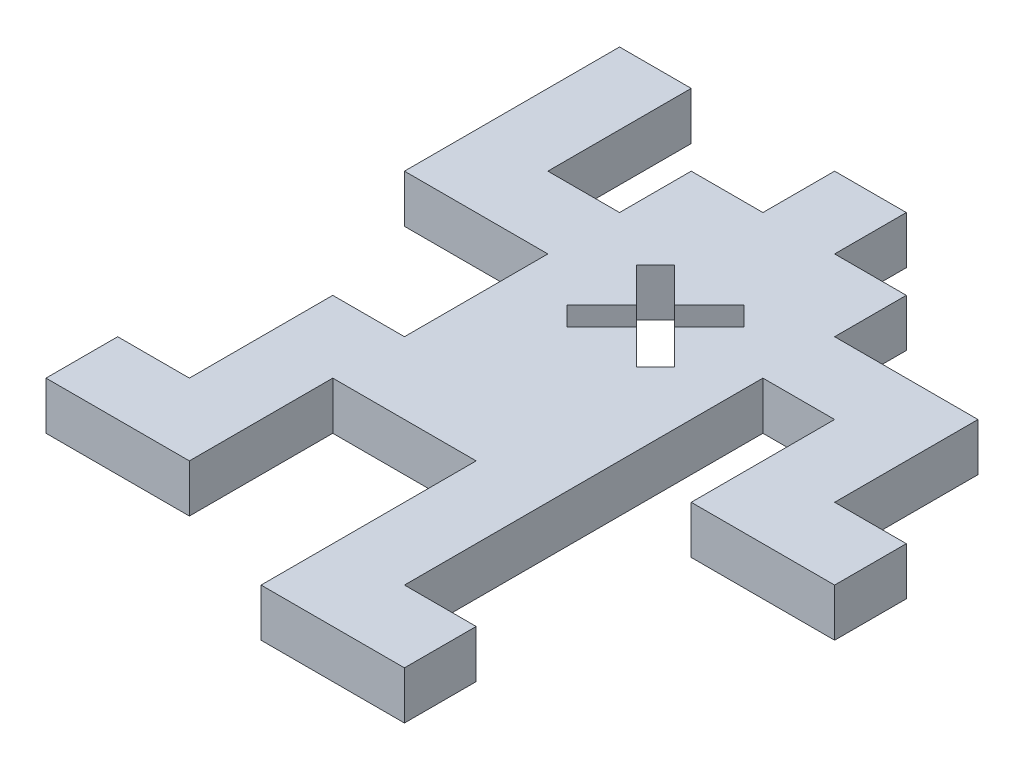
SolidWorks part; units mm, degrees
ref_plane "Front Plane" through (0, 0, 0) normal (0, 0, 1) x (1, 0, 0)
ref_plane "Top Plane" through (0, 0, 0) normal (0, 1, 0) x (1, 0, 0)
ref_plane "Right Plane" through (0, 0, 0) normal (1, 0, 0) x (0, 0, -1)
sketch "Sketch1" plane through (0, 0, 0) normal (0, 1, 0) x (1, 0, 0)
  line L0 (-11.25, 11.25) -> (-18.75, 11.25)
  line L1 (-11.25, 18.75) -> (11.25, 18.75)
  line L2 (-11.25, 18.75) -> (-11.25, -18.75)
  line L3 (-11.25, -18.75) -> (11.25, -18.75)
  line L4 (11.25, 18.75) -> (11.25, -18.75)
  line L5 (-11.25, 18.75) -> (11.25, -18.75) construction
  line L6 (-11.25, -18.75) -> (11.25, 18.75) construction
  line L7 (-3.75, 18.75) -> (3.75, 18.75)
  line L8 (-3.75, 18.75) -> (-3.75, 26.25)
  line L9 (-3.75, 26.25) -> (3.75, 26.25)
  line L10 (3.75, 18.75) -> (3.75, 26.25)
  line L11 (-18.75, 11.25) -> (-18.75, 26.25)
  line L12 (-18.75, 26.25) -> (-26.25, 26.25)
  line L13 (-26.25, 26.25) -> (-26.25, 3.75)
  line L14 (-26.25, 3.75) -> (-11.25, 3.75)
  line L15 (11.25, 11.25) -> (26.25, 11.25)
  line L16 (26.25, 11.25) -> (26.25, -3.75)
  line L17 (26.25, -3.75) -> (33.75, -3.75)
  line L18 (33.75, -3.75) -> (33.75, -11.25)
  line L19 (33.75, -11.25) -> (18.75, -11.25)
  line L20 (18.75, -11.25) -> (18.75, 3.75)
  line L21 (18.75, 3.75) -> (11.25, 3.75)
  line L22 (11.25, -18.75) -> (11.25, -33.75)
  line L23 (11.25, -33.75) -> (18.75, -33.75)
  line L24 (18.75, -33.75) -> (18.75, -41.25)
  line L25 (18.75, -41.25) -> (3.75, -41.25)
  line L26 (3.75, -41.25) -> (3.75, -18.75)
  line L27 (-11.25, -18.75) -> (-11.25, -33.75)
  line L28 (-11.25, -33.75) -> (-26.25, -33.75)
  line L29 (-26.25, -33.75) -> (-26.25, -26.25)
  line L30 (-26.25, -26.25) -> (-18.75, -26.25)
  line L31 (-18.75, -26.25) -> (-18.75, -11.25)
  line L32 (-18.75, -11.25) -> (-11.25, -11.25)
  point P0 (0, 0)
  dimension "D1" = 37.5
  dimension "D2" = 22.5
  dimension "D3" = 7.5
  dimension "D4" = 7.5
  dimension "D5" = 7.5
  dimension "D6" = 7.5
  dimension "D7" = 7.5
  dimension "D8" = 7.5
  dimension "D9" = 15
  dimension "D10" = 15
  dimension "D11" = 7.5
  dimension "D12" = 7.5
  dimension "D13" = 15
  dimension "D14" = 22.5
  dimension "D15" = 22.5
  dimension "D16" = 7.5
  dimension "D17" = 15
  dimension "D18" = 15
  dimension "D19" = 15
  dimension "D20" = 7.5
  dimension "D21" = 15
  dimension "D22" = 15
  dimension "D23" = 7.5
extrude "Boss-Extrude1" add sketch "Sketch1" along normal blind 5 contours L13 L14 L2 L0 L11 L12 | L4 L1 L2 L3 | L1 L10 L9 L8 | L21 L20 L19 L18 L17 L16 L15 L4 | L26 L25 L24 L23 L22 L3 | L32 L31 L30 L29 L28 L27 L2
sketch "Sketch2" plane through (0, 5, 0) normal (0, 1, 0) x (1, 0, 0)
  line L0 (-11.25, 11.25) -> (11.25, 11.25) construction
  line L3 (-11.25, -3.75) -> (11.25, -3.75) construction
  line L4 (-11.25, 3.75) -> (-11.25, -11.25) construction
  line L5 (11.25, 3.75) -> (11.25, -33.75) construction
  line L6 (0, 11.25) -> (0, -3.75) construction
  line L7 (0, 5.75) -> (-3.625, 9.375)
  line L8 (-3.625, 9.375) -> (-5.625, 7.375)
  line L9 (-5.625, 7.375) -> (-2, 3.75)
  line L10 (-2, 3.75) -> (-5.625, 0.125)
  line L11 (-5.625, 0.125) -> (-3.625, -1.875)
  line L12 (-3.625, -1.875) -> (0, 1.75)
  line L13 (0, 5.75) -> (0, 1.75) construction
  line L14 (3.625, -1.875) -> (0, 1.75)
  line L15 (5.625, 0.125) -> (3.625, -1.875)
  line L16 (2, 3.75) -> (5.625, 0.125)
  line L17 (5.625, 7.375) -> (2, 3.75)
  line L18 (3.625, 9.375) -> (5.625, 7.375)
  line L19 (0, 5.75) -> (3.625, 9.375)
  point P25 (0, 3.75)
  dimension "D1" = 45
  dimension "D3" = 1.875
  dimension "D4" = 4
  dimension "D2" = 2
extrude "Cut-Extrude1" cut sketch "Sketch2" against normal through all
equation "\"Square Width\" = 7.5mm"
equation "\"Square Height\"= 7.5mm"
equation "\"Tolerance\"= 1mm"
equation "\"Block Height\" = 5mm"
equation "\"Base Height\"= 10mm"
equation "\"D1@Sketch1\"=\"Square Height\"*5"
equation "\"D2@Sketch1\"=\"Square Width\"*3"
equation "\"D3@Sketch1\"=\"Square Width\""
equation "\"D4@Sketch1\"=\"Square Height\""
equation "\"D5@Sketch1\"=\"Square Width\""
equation "\"D6@Sketch1\"=\"Square Height\""
equation "\"D7@Sketch1\"=\"Square Height\""
equation "\"D8@Sketch1\"=\"Square Width\""
equation "\"D9@Sketch1\"=\"Square Width\"*2"
equation "\"D10@Sketch1\"=\"Square Width\"*2"
equation "\"D11@Sketch1\"=\"Square Width\""
equation "\"D12@Sketch1\"=\"Square Height\""
equation "\"D13@Sketch1\"=\"Square Width\"*2"
equation "\"D14@Sketch1\"=\"Square Height\"*3"
equation "\"D15@Sketch1\"=\"Square Height\"*3"
equation "\"D16@Sketch1\"=\"Square Width\""
equation "\"D17@Sketch1\"=\"Square Height\"*2"
equation "\"D18@Sketch1\"=\"Square Width\"*2"
equation "\"D19@Sketch1\"=\"Square Height\"*2"
equation "\"D20@Sketch1\"=\"Square Height\""
equation "\"D21@Sketch1\"=\"Square Height\"*2"
equation "\"D22@Sketch1\"=\"Square Width\"*2"
equation "\"D23@Sketch1\"=\"Square Width\""
equation "\"D1@Boss-Extrude1\"=\"Block Height\""
equation "\"D3@Sketch2\"=\"Square Height\"/4"
